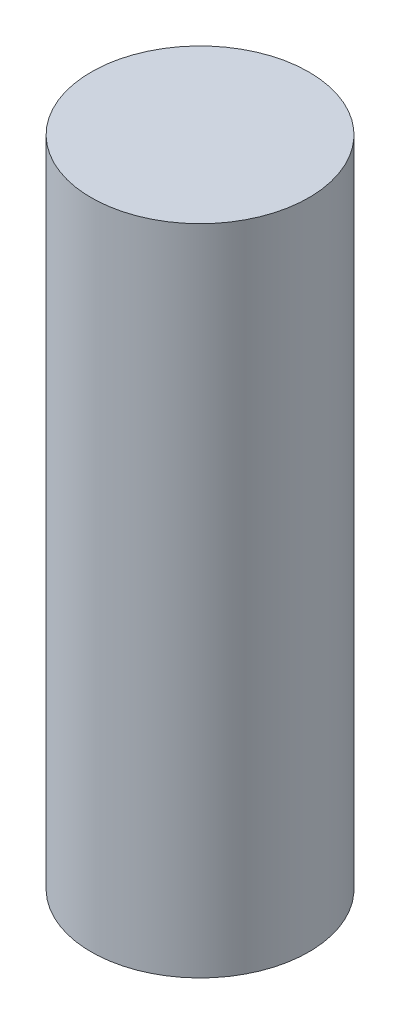
SolidWorks part; units mm, degrees
material "Alloy Steel"
ref_plane "Front" through (0, 0, 0) normal (0, 0, 1) x (1, 0, 0)
ref_plane "Top" through (0, 0, 0) normal (0, 1, 0) x (1, 0, 0)
ref_plane "Right" through (0, 0, 0) normal (1, 0, 0) x (0, 0, -1)
sketch "Sketch1" plane through (0, 0, 0) normal (0, 1, 0) x (1, 0, 0)
  circle A0 centre (0, 0) radius 1.5875
  dimension "D1" = 3.175
extrude "Boss-Extrude1" add sketch "Sketch1" along normal mid plane 9.525
